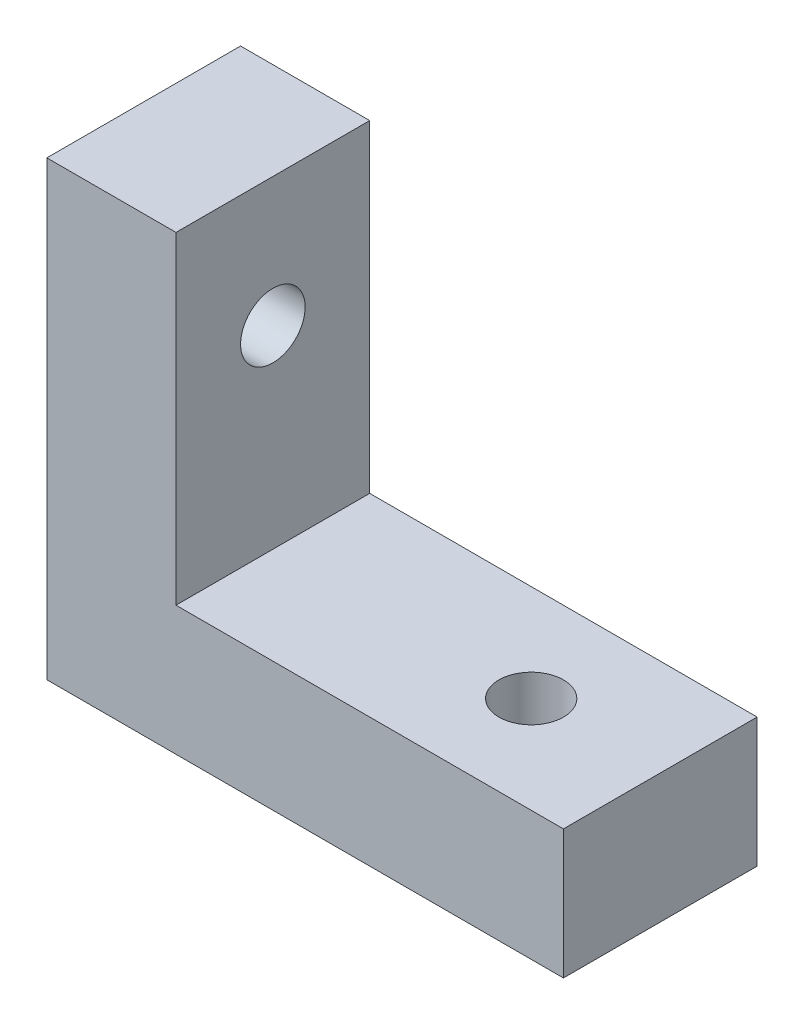
SolidWorks part; units mm, degrees
ref_plane "Front Plane" through (0, 0, 0) normal (0, 0, 1) x (1, 0, 0)
ref_plane "Top Plane" through (0, 0, 0) normal (0, 1, 0) x (1, 0, 0)
ref_plane "Right Plane" through (0, 0, 0) normal (1, 0, 0) x (0, 0, -1)
sketch "Sketch1" plane through (0, 0, 0) normal (0, 1, 0) x (1, 0, 0)
  line L0 (0, 0) -> (80, 0)
  line L1 (80, 0) -> (80, 30)
  line L2 (80, 30) -> (0, 30)
  line L3 (0, 30) -> (0, 0)
  dimension "D1" = 80
  dimension "D2" = 30
extrude "Boss-Extrude2" add sketch "Sketch1" along normal blind 20
sketch "Sketch4" plane through (0, 20, 0) normal (0, 1, 0) x (1, 0, 0)
  line L0 (-6.1646, 15) -> (89.156, 15) construction
  line L3 (0, 30) -> (20, 30)
  line L4 (0, 30) -> (0, 0)
  line L5 (0, 0) -> (20, 0)
  line L6 (20, 30) -> (20, 0)
  line L7 (0, 0) -> (80, 0) construction
  circle A0 centre (60, 15) radius 5
  dimension "D2" = 10
  dimension "D3" = 20
  dimension "D1" = 30
extrude "Boss-Extrude3" add sketch "Sketch4" along normal blind 50 contours L4 L3 L6 L5
sketch "Sketch6" plane through (0, 20, 0) normal (0, 1, 0) x (1, 0, 0)
  circle A0 centre (60.0182, 14.9932) radius 5
  dimension "D1" = 10
extrude "Cut-Extrude2" cut sketch "Sketch6" against normal blind 50
sketch "Sketch7" plane through (20, 0, 0) normal (1, 0, 0) x (0, 0, -1)
  circle A0 centre (15, 50) radius 5
  dimension "D2" = 10
extrude "Cut-Extrude4" cut sketch "Sketch7" against normal blind 50
